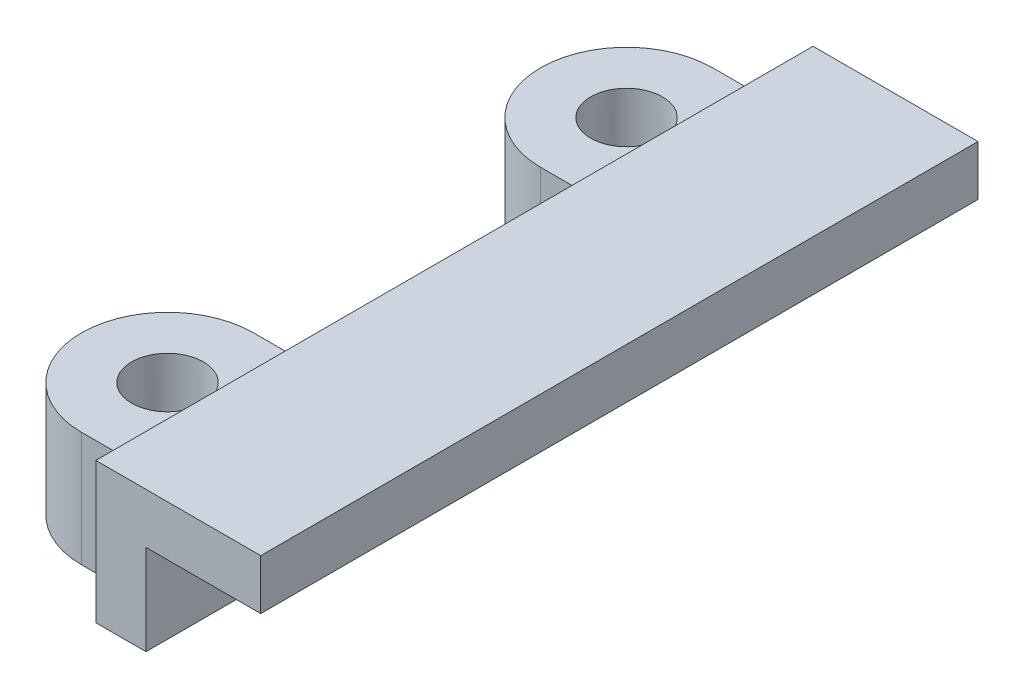
SolidWorks part; units mm, degrees
ref_plane "Alzado" through (0, 0, 0) normal (0, 0, 1) x (1, 0, 0)
ref_plane "Planta" through (0, 0, 0) normal (0, 1, 0) x (1, 0, 0)
ref_plane "Vista lateral" through (0, 0, 0) normal (1, 0, 0) x (0, 0, -1)
sketch "Croquis1" plane through (0, 0, 0) normal (0, 0, 1) x (1, 0, 0)
  line L0 (0, 0) -> (0, 9.8)
  line L1 (0, 9.8) -> (11.5, 9.8)
  line L2 (11.5, 9.8) -> (11.5, 6.3)
  line L3 (11.5, 6.3) -> (3.5, 6.3)
  line L4 (3.5, 6.3) -> (3.5, 0)
  line L5 (3.5, 0) -> (0, 0)
  dimension "D1" = 6.3
  dimension "D2" = 3.5
  dimension "D3" = 8
  dimension "D4" = 3.5
sketch "Croquis3" plane through (0, 0, 0) normal (0, 1, 0) x (1, 0, 0)
  line L0 (0, 0) -> (0, -37)
  dimension "D1" = 37
sweep "Barrer1" add profiles "Croquis1" path "Croquis3"
ref_plane "Plano1" through (80.5, 0, 0) normal (-1, 0, 0) x (0, 0, 1)
sketch "Croquis4" plane through (0, 0, 0) normal (-1, 0, 0) x (0, 0, 1)
  line L0 (0, 0) -> (37, 0) construction
  line L1 (37, 9.8) -> (50, 9.8)
  line L2 (37, 9.8) -> (37, 0)
  line L3 (37, 0) -> (50, 0)
  line L4 (50, 9.8) -> (50, 0)
  dimension "D1" = 13
extrude "Saliente-Extruir1" add sketch "Croquis4" against normal blind 161
mirror "Simetría5" about plane through (80.5, 0, 0) normal (-1, 0, 0) of "Barrer1"
sketch "Croquis5" plane through (0, 0, 0) normal (0, -1, 0) x (1, 0, 0)
  line L1 (3.5, 37) -> (154.5, 37)
  line L2 (3.5, 37) -> (3.5, 40.5)
  line L3 (3.5, 40.5) -> (154.5, 40.5)
  line L4 (154.5, 37) -> (154.5, 40.5)
  dimension "D1" = 3.5
  dimension "D2" = 151
extrude "Cortar-Extruir1" cut sketch "Croquis5" against normal blind 6.3
sketch "Croquis6" plane through (0, 0, 50) normal (0, 0, 1) x (1, 0, 0)
  line L0 (161, 9.8) -> (0, 9.8) construction
  line L1 (16, 9.8) -> (26, 9.8)
  line L2 (16, 9.8) -> (16, 12.5)
  line L4 (26, 9.8) -> (26, 12.5)
  line L5 (0, 0) -> (0, 9.8) construction
  arc A0 (26, 12.5) -> (16, 12.5) centre (21, 12.5) ccw
  dimension "D1" = 2.7
  dimension "D2" = 10
  dimension "D3" = 21
extrude "Saliente-Extruir2" [suppressed] add sketch "Croquis6" against normal blind 10
sketch "Croquis7" [suppressed] plane through (0, 0, 50) normal (0, 0, 1) x (1, 0, 0)
  circle A0 centre (21, 14) radius 3
  dimension "D1" = 6
extrude "Cortar-Extruir2" [suppressed] cut sketch "Croquis7" against normal through all
mirror "Simetría6" [suppressed] about plane through (80.5, 0, 0) normal (-1, 0, 0)
sketch "Croquis8" plane through (0, 0, 0) normal (0, -1, 0) x (1, 0, 0)
  line L0 (161, 0) -> (161, 50) construction
  line L1 (161, 47) -> (165, 47)
  line L2 (161, 47) -> (161, 35)
  line L3 (161, 35) -> (165, 35)
  line L5 (161, 50) -> (0, 50) construction
  arc A0 (165, 35) -> (165, 47) centre (165, 41) ccw
  dimension "D1" = 4
  dimension "D2" = 12
  dimension "D3" = 9
extrude "Saliente-Extruir3" add sketch "Croquis8" against normal blind 8
sketch "Croquis9" plane through (0, 0, 0) normal (0, -1, 0) x (1, 0, 0)
  circle A0 centre (165, 41) radius 2.5
  dimension "D1" = 5
extrude "Cortar-Extruir3" cut sketch "Croquis9" against normal through all
ref_plane "Plano2" through (0, 0, 25) normal (0, 0, -1) x (-1, 0, 0)
mirror "Simetría7" about plane through (0, 0, 25) normal (0, 0, -1) of "Saliente-Extruir3", "Cortar-Extruir3"
mirror "Simetría8" about plane through (80.5, 0, 0) normal (-1, 0, 0) of "Simetría7", "Saliente-Extruir3", "Cortar-Extruir3"
sketch "Croquis10" plane through (0, 9.8, 0) normal (0, 1, 0) x (1, 0, 0)
  line L0 (161, -50) -> (161, 0) construction
  line L1 (161, -50) -> (0, -50) construction
  circle A0 centre (121, -45.25) radius 2.5
  dimension "D3" = 5
  dimension "D1" = 40
  dimension "D2" = 4.75
extrude "Cortar-Extruir4" cut sketch "Croquis10" against normal through all
pattern_linear "MatrizL1" count 3 spacing 40.5 along (-1, 0, 0) of "Cortar-Extruir4"
ref_plane "Plano3" through (11.5, 0, 0) normal (1, 0, 0) x (0, 0, -1)
sketch "Croquis11" plane through (11.5, 0, 0) normal (1, 0, 0) x (0, 0, -1)
  line L1 (-59.3834, 19.3777) -> (5.4703, 19.3777)
  line L2 (-59.3834, 19.3777) -> (-59.3834, -3.5873)
  line L3 (-59.3834, -3.5873) -> (5.4703, -3.5873)
  line L4 (5.4703, 19.3777) -> (5.4703, -3.5873)
extrude "Cortar-Extruir5" cut sketch "Croquis11" along normal through all
sketch "Croquis12" plane through (0, 0, 40.5) normal (0, 0, -1) x (-1, 0, 0)
  line L4 (-11.5, 6.3) -> (-11.5, 0)
  line L5 (-11.5, 0) -> (-3.5, 0)
  line L6 (-3.5, 0) -> (-3.5, 6.3)
  line L7 (-3.5, 6.3) -> (-11.5, 6.3)
  line L8 (-11.5, 6.3) -> (-11.5, 0)
  line L9 (-11.5, 0) -> (-3.5, 0)
  line L10 (-3.5, 0) -> (-3.5, 6.3)
  line L11 (-3.5, 6.3) -> (-11.5, 6.3)
  dimension "D1" = 0
extrude "Cortar-Extruir6" cut sketch "Croquis12" against normal through all
ref_plane "Plano4" through (0, 0, 25) normal (0, 0, -1) x (-1, 0, 0)
